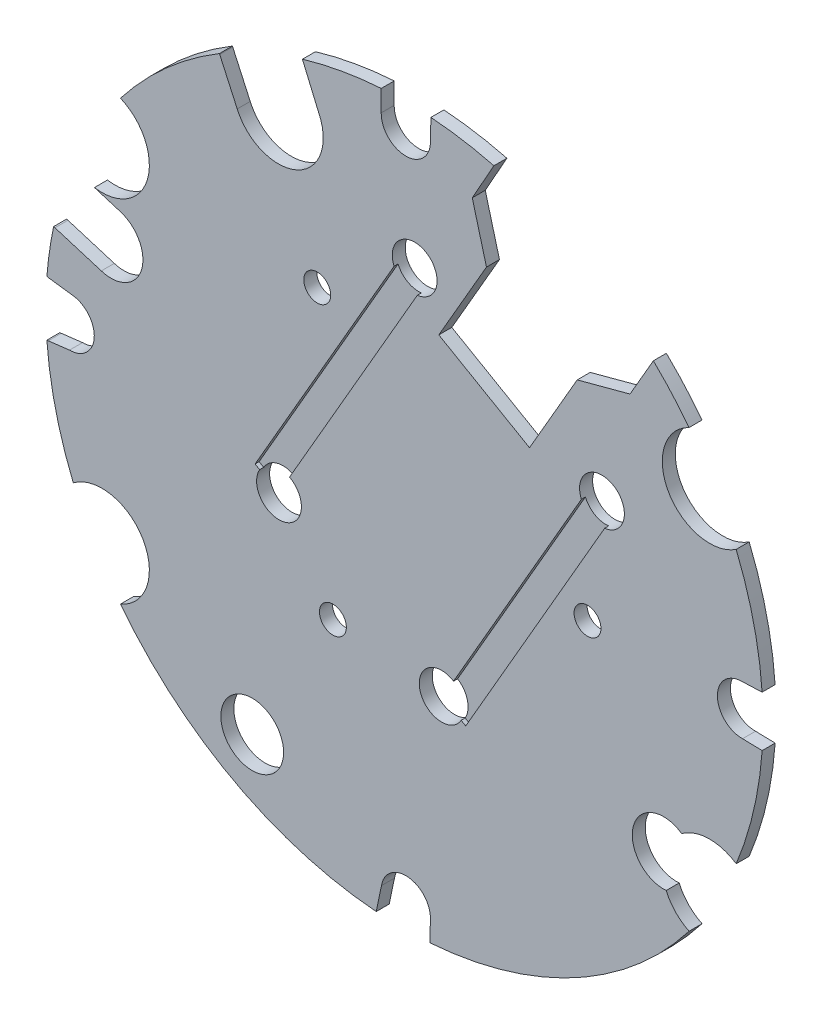
SolidWorks part; units mm, degrees
ref_plane "Płaszczyzna przednia" through (0, 0, 0) normal (0, 0, 1) x (1, 0, 0)
ref_plane "Płaszczyzna górna" through (0, 0, 0) normal (0, 1, 0) x (1, 0, 0)
ref_plane "Płaszczyzna prawa" through (0, 0, 0) normal (1, 0, 0) x (0, 0, -1)
sketch "Szkic1" plane through (0, 0, 0) normal (0, 0, 1) x (1, 0, 0)
  line L50 (5.5961, 79.7937) -> (5.4745, 74.546)
  line L51 (-5.4929, 75.1289) -> (-5.4929, 79.8443)
  line L52 (-23.0659, 76.7087) -> (-23.04, 76.6214)
  line L53 (-23.04, 76.6214) -> (-19.4116, 68.1275)
  line L54 (-37.6167, 59.8245) -> (-41.5257, 68.3953)
  line L55 (-41.5257, 68.3953) -> (-41.5818, 68.5478)
  line L56 (-69.476, 28.7032) -> (-63.7823, 26.9624)
  line L57 (-67.9444, 13.361) -> (-78.2861, 16.5229)
  line L58 (-78.2861, 16.5229) -> (-78.5826, 16.6056)
  line L59 (-80.08, 6.2528) -> (-79.773, 6.1541)
  line L60 (-79.773, 6.1541) -> (-74.6773, 5.4836)
  line L61 (-75.0381, -5.4931) -> (-79.7769, -6.0604)
  line L62 (-79.7769, -6.0604) -> (-80.0922, -6.0956)
  line L63 (-6.5994, -79.7648) -> (-6.5994, -79.7341)
  line L64 (-6.5994, -79.7341) -> (-5.4277, -74.1539)
  line L65 (5.491, -75.1576) -> (5.3574, -79.811)
  line L66 (79.5031, -5.6051) -> (75.1326, -5.4981)
  line L67 (75.0191, 5.4985) -> (79.4978, 5.6797)
  line L68 (55.2372, 57.5863) -> (50.0191, 48.5483)
  line L69 (50.0191, 48.5483) -> (38.2358, 45.391)
  line L70 (38.2358, 45.391) -> (27.5975, 26.965)
  line L71 (27.5975, 26.965) -> (7.3602, 38.649)
  line L72 (7.3602, 38.649) -> (17.9935, 57.0663)
  line L73 (17.9935, 57.0663) -> (14.8238, 68.8683)
  line L74 (14.8238, 68.8683) -> (19.6536, 77.481)
  circle A3 centre (-16.27, -28.1805) radius 3
  circle A4 centre (40.54, 0) radius 3
  circle A5 centre (-19.77, 34.2427) radius 3
  arc A40 (19.6536, 77.481) -> (5.5961, 79.7937) centre (-0.3125, 0) ccw
  arc A41 (-5.4929, 75.1289) -> (5.4745, 74.546) centre (0.0001, 75.0129) ccw
  arc A42 (-5.4929, 79.8443) -> (-23.0659, 76.7087) centre (-0.3125, 0) ccw
  arc A43 (-37.6167, 59.8245) -> (-19.4116, 68.1275) centre (-28.4334, 63.799) ccw
  arc A44 (-41.5818, 68.5478) -> (-63.6618, 48.8755) centre (-0.3125, 0) ccw
  arc A45 (-69.476, 28.7032) -> (-63.6618, 48.8755) centre (-67.7996, 39.1441) ccw
  arc A46 (-67.9444, 13.361) -> (-63.7823, 26.9624) centre (-65.7723, 20.1338) ccw
  arc A47 (-78.5826, 16.6056) -> (-80.08, 6.2528) centre (-0.3125, 0) ccw
  arc A48 (-75.0381, -5.4931) -> (-74.6773, 5.4836) centre (-75.0033, 0) ccw
  arc A49 (-80.0922, -6.0956) -> (-74.1921, -30.7205) centre (-0.3125, 0) ccw
  arc A50 (-63.6618, -48.8755) -> (-74.1921, -30.7205) centre (-67.7996, -39.1441) ccw
  arc A51 (-63.6618, -48.8755) -> (-6.5994, -79.7648) centre (-0.3125, 0) ccw
  arc A52 (5.491, -75.1576) -> (-5.4277, -74.1539) centre (-0.001, -75.0109) ccw
  arc A53 (5.3574, -79.811) -> (63.1984, -48.6652) centre (-0.3125, 0) ccw
  arc A54 (73.7097, -30.3753) -> (63.1984, -48.6652) centre (67.7996, -39.1441) ccw
  arc A55 (73.7097, -30.3753) -> (79.5031, -5.6051) centre (-0.3125, 0) ccw
  arc A56 (75.0191, 5.4985) -> (75.1326, -5.4981) centre (75.0176, -0.0004) ccw
  arc A57 (79.4978, 5.6797) -> (73.7097, 30.3753) centre (-0.3125, 0) ccw
  arc A58 (63.1984, 48.6652) -> (73.7097, 30.3753) centre (67.7996, 39.1441) ccw
  arc A59 (63.1984, 48.6652) -> (55.2372, 57.5863) centre (-0.3125, 0) ccw
extrude "Dodanie-wyciągnięcie1" add sketch "Szkic1" along normal blind 2.9
sketch "pomoc1" plane through (0, 0, 2.9) normal (0, 0, 1) x (1, 0, 0)
  line L0 (-16.27, -28.1805) -> (0, 0) construction
  line L1 (-19.77, 34.2427) -> (0, 0) construction
  line L2 (0, 0) -> (40.54, 0) construction
  line L3 (1.9716, 48.8729) -> (43.766, 24.7429)
  line L4 (1.9716, 48.8729) -> (-31.0284, -8.2848)
  line L5 (43.766, 24.7429) -> (10.766, -32.4148)
  line L6 (-31.0284, -8.2848) -> (10.766, -32.4148)
  circle A0 centre (1.9716, 48.8729) radius 1.5
  circle A1 centre (43.766, 24.7429) radius 2
  dimension "D6" = 3
  dimension "D7" = 4
  dimension "D1" = 120
  dimension "D2" = 39.54
  dimension "D3" = 40.54
  dimension "D4" = 32.54
  dimension "D5" = 66
sketch "Sketch2" plane through (0, 0, 2.9) normal (0, 0, 1) x (1, 0, 0)
  line L0 (-16.27, -28.1805) -> (0, 0) construction
  line L1 (-19.77, 34.2427) -> (0, 0) construction
  line L2 (0, 0) -> (40.54, 0) construction
  line L3 (1.9716, 48.8729) -> (43.766, 24.7429) construction
  line L4 (1.9716, 48.8729) -> (-31.0284, -8.2848) construction
  line L5 (43.766, 24.7429) -> (10.766, -32.4148) construction
  line L6 (-31.0284, -8.2848) -> (10.766, -32.4148) construction
  line L7 (44.3641, 19.7788) -> (13.3641, -33.9148)
  line L8 (4.7216, 47.2852) -> (4.7216, 50.4606) construction
  line L9 (4.7216, 50.4606) -> (1.9716, 52.0484) construction
  line L10 (1.9716, 52.0484) -> (-0.7784, 50.4606) construction
  line L11 (-0.7784, 50.4606) -> (-0.7784, 47.2852) construction
  line L12 (-0.7784, 47.2852) -> (1.9716, 45.6975) construction
  line L13 (1.9716, 45.6975) -> (4.7216, 47.2852) construction
  line L14 (39.1679, 22.7788) -> (10.6464, -26.6219)
  line L15 (4.5697, 47.3729) -> (4.4178, 47.1098)
  line L16 (-0.6265, 50.3729) -> (-0.7784, 50.1098)
  line L17 (-33.6265, -6.7848) -> (-32.6126, -7.3789)
  line L18 (13.3641, -33.9148) -> (12.3464, -33.3272)
  line L19 (46.3641, 23.2429) -> (13.3641, -33.9148) construction
  line L20 (41.1679, 26.2429) -> (8.1679, -30.9148) construction
  line L21 (-2.6265, 46.9088) -> (-33.6265, -6.7848)
  line L22 (4.5697, 47.3729) -> (-28.4303, -9.7848) construction
  line L23 (-0.6265, 50.3729) -> (-33.6265, -6.7848) construction
  line L24 (2.5697, 43.9088) -> (-25.9518, -5.4919)
  circle A2 centre (43.766, 24.7429) radius 1.5875 construction
  circle A3 centre (1.9716, 48.8729) radius 1.5875
  circle A6 centre (7.9964, -30.8619) radius 1.5875 construction
  circle A7 centre (-28.2988, -9.9069) radius 1.5875 construction
  circle A8 centre (1.9716, 48.8729) radius 2.75 construction
  arc A9 (2.5697, 43.9088) -> (-2.6265, 46.9088) centre (1.9716, 48.8729) ccw
  arc A10 (44.3641, 19.7788) -> (39.1679, 22.7788) centre (43.766, 24.7429) ccw
  arc A11 (-32.6126, -7.3789) -> (-25.9518, -5.4919) centre (-28.2988, -9.9069) ccw
  arc A12 (10.6464, -26.6219) -> (12.3464, -33.3272) centre (7.9964, -30.8619) ccw
  dimension "D6" = 5.5
  dimension "D7" = 10
  dimension "D8" = 10
  dimension "D9" = 10
  dimension "D10" = 10
  dimension "D1" = 120
  dimension "D2" = 39.54
  dimension "D3" = 40.54
  dimension "D4" = 32.54
  dimension "D5" = 66
  dimension "D11" = 3
  dimension "D12" = 3
  dimension "D13" = 3
  dimension "D14" = 3
extrude "Cut-Extrude1" cut sketch "Sketch2" against normal through all contours L21 L17 A11 L24 A9 | L14 A12 L18 L7 A10
sketch "Sketch3" plane through (0, 0, 0) normal (0, 0, -1) x (-1, 0, 0)
  line L0 (2.6265, 46.9088) -> (33.6265, -6.7848) construction
  line L1 (33.6265, -6.7848) -> (32.6126, -7.3789) construction
  line L2 (-2.5697, 43.9088) -> (25.9518, -5.4919) construction
  line L3 (-39.1679, 22.7788) -> (-10.6464, -26.6219) construction
  line L4 (-13.3641, -33.9148) -> (-12.3464, -33.3272) construction
  line L5 (-44.3641, 19.7788) -> (-13.3641, -33.9148) construction
  line L6 (2.6265, 46.9088) -> (33.6265, -6.7848)
  line L7 (33.6265, -6.7848) -> (32.6126, -7.3789)
  line L8 (-2.5697, 43.9088) -> (25.9518, -5.4919)
  line L9 (-39.1679, 22.7788) -> (-10.6464, -26.6219)
  line L10 (-13.3641, -33.9148) -> (-12.3464, -33.3272)
  line L11 (-44.3641, 19.7788) -> (-13.3641, -33.9148)
  arc A0 (-44.3641, 19.7788) -> (-39.1679, 22.7788) centre (-43.766, 24.7429) ccw
  arc A1 (-2.5697, 43.9088) -> (2.6265, 46.9088) centre (-1.9716, 48.8729) ccw
  arc A2 (32.6126, -7.3789) -> (25.9518, -5.4919) centre (28.2988, -9.9069) ccw
  arc A3 (-10.6464, -26.6219) -> (-12.3464, -33.3272) centre (-7.9964, -30.8619) ccw
extrude "Boss-Extrude1" add sketch "Sketch3" against normal blind 2
sketch "Sketch4" plane through (0, 0, 2.9) normal (0, 0, 1) x (1, 0, 0)
  line L0 (0, 0) -> (-37.9499, -65.7311) construction
  line L1 (0, 0) -> (62.3558, -36.0011) construction
  line L2 (40.54, 0) -> (70.7379, -17.4348) construction
  line L3 (29.04, -19.9186) -> (59.2379, -37.3534) construction
  line L4 (58.8897, -34) -> (57.5247, -36.3642) construction
  circle A0 centre (-34.27, -59.3574) radius 7
  circle A1 centre (-16.27, -28.1805) radius 3 construction
  circle A2 centre (58.8897, -34) radius 7 construction
  circle A3 centre (40.54, 0) radius 3 construction
  circle A4 centre (57.5247, -36.3642) radius 7
  dimension "D1" = 14
  dimension "D3" = 14
  dimension "D4" = 68
  dimension "D7" = 14
  dimension "D2" = 36
  dimension "D5" = 20.27
  dimension "D6" = 23
extrude "Cut-Extrude2" cut sketch "Sketch4" against normal through all
sketch "odbitka na EB" plane through (0, 0, 2.9) normal (0, 0, 1) x (1, 0, 0)
  line L0 (39.1679, 22.7788) -> (10.6464, -26.6219) construction
  line L1 (44.3641, 19.7788) -> (13.3641, -33.9148) construction
  line L2 (13.3641, -33.9148) -> (12.3464, -33.3272) construction
  line L3 (2.5697, 43.9088) -> (-25.9518, -5.4919) construction
  line L4 (-2.6265, 46.9088) -> (-33.6265, -6.7848) construction
  line L5 (-33.6265, -6.7848) -> (-32.6126, -7.3789) construction
  line L6 (39.1679, 22.7788) -> (10.6464, -26.6219)
  line L7 (44.3641, 19.7788) -> (13.3641, -33.9148)
  line L8 (13.3641, -33.9148) -> (12.3464, -33.3272)
  line L9 (2.5697, 43.9088) -> (-25.9518, -5.4919)
  line L10 (-2.6265, 46.9088) -> (-33.6265, -6.7848)
  line L11 (-33.6265, -6.7848) -> (-32.6126, -7.3789)
  arc A0 (10.6464, -26.6219) -> (12.3464, -33.3272) centre (7.9964, -30.8619) ccw construction
  arc A1 (-32.6126, -7.3789) -> (-25.9518, -5.4919) centre (-28.2988, -9.9069) ccw construction
  arc A2 (44.3641, 19.7788) -> (39.1679, 22.7788) centre (43.766, 24.7429) ccw construction
  arc A3 (2.5697, 43.9088) -> (-2.6265, 46.9088) centre (1.9716, 48.8729) ccw construction
  arc A4 (10.6464, -26.6219) -> (12.3464, -33.3272) centre (7.9964, -30.8619) ccw
  arc A5 (-32.6126, -7.3789) -> (-25.9518, -5.4919) centre (-28.2988, -9.9069) ccw
  arc A6 (44.3641, 19.7788) -> (39.1679, 22.7788) centre (43.766, 24.7429) ccw
  arc A7 (2.5697, 43.9088) -> (-2.6265, 46.9088) centre (1.9716, 48.8729) ccw
  point P0 (0, 0)
